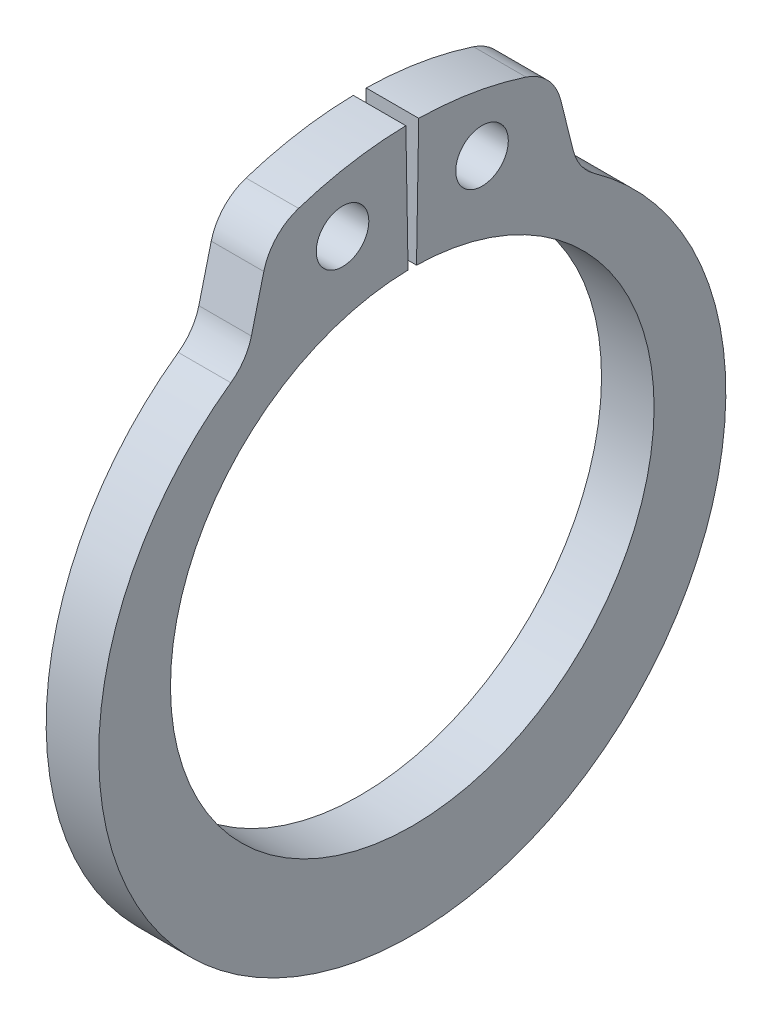
SolidWorks part; units mm, degrees
material "Cast Carbon Steel"
ref_plane "Front" through (0, 0, 0) normal (0, 0, 1) x (1, 0, 0)
ref_plane "Top" through (0, 0, 0) normal (0, 1, 0) x (1, 0, 0)
ref_plane "Right" through (0, 0, 0) normal (1, 0, 0) x (0, 0, -1)
sketch "Sketch1" plane through (0, 0, 0) normal (1, 0, 0) x (0, 0, -1)
  line L0 (0, 0) -> (0, 5.842) construction
  line L1 (-0.102, 5.8411) -> (-0.1552, 8.8886)
  line L2 (-0.1552, 8.8886) -> (-3.268, 8.8343) construction
  line L3 (-3.268, 8.8343) -> (-4.0054, 5.8768) construction
  line L4 (0.1552, 8.8886) -> (0.102, 5.8411)
  line L5 (0.1552, 8.8886) -> (3.268, 8.8343) construction
  line L6 (3.268, 8.8343) -> (4.0054, 5.8768) construction
  line L7 (-4.0054, 5.8768) -> (-3.2901, 4.8274) construction
  line L8 (4.0054, 5.8768) -> (3.2901, 4.8274) construction
  line L9 (0, -5.842) -> (0, -8.128) construction
  line L10 (-3.268, 8.8343) -> (-0.102, 5.8411) construction
  line L11 (-5.842, 0) -> (5.842, 0) construction
  line L12 (0, 5.842) -> (0, 8.89) construction
  line L13 (3.4253, 8.2036) -> (4.0054, 5.8768)
  line L14 (-3.4253, 8.2036) -> (-4.0054, 5.8768)
  circle A0 centre (0, 0) radius 5.842 construction
  arc A1 (-0.102, 5.8411) -> (0.102, 5.8411) centre (0, 0) ccw
  circle A2 centre (0, -0.5528) radius 7.5752 construction
  circle A3 centre (0, 0) radius 8.89 construction
  circle A4 centre (-1.685, 7.3377) radius 0.635
  circle A5 centre (1.685, 7.3377) radius 0.635
  arc A6 (-4.0054, 5.8768) -> (4.0054, 5.8768) centre (0, -0.5528) ccw
  arc A7 (0.1552, 8.8886) -> (3.4253, 8.2036) centre (0, 0) cw
  arc A8 (-0.1552, 8.8886) -> (-3.4253, 8.2036) centre (0, 0) ccw
  dimension "D1" = 75
  dimension "A" = 11.684
  dimension "L" = 17.78
  dimension "Hole" = 1.27
  dimension "Smin" = 1.27
  dimension "Smax" = 2.286
  dimension "H" = 3.048
  dimension "Angle" = 1
extrude "Extrude1" add sketch "Sketch1" along normal mid plane 1.27
fillet "Fillet1" radius 1.27 4 edges at (0, 5.8768, 4.0054) (0, 8.2036, 3.4253) (0, 8.2036, -3.4253) (0, 5.8768, -4.0054)
sketch "Sketch2" plane through (0, 0, 0) normal (0, 0, 1) x (1, 0, 0)
  line L0 (-3.556, 0) -> (10.668, 0)
  line L1 (10.668, 0) -> (10.668, -6.35)
  line L3 (10.668, -6.35) -> (0.7112, -6.35)
  line L4 (0.7112, -6.35) -> (0.7112, -5.9436)
  line L5 (0.7112, -5.9436) -> (-0.7112, -5.9436)
  line L6 (-0.7112, -5.9436) -> (-0.7112, -6.35)
  line L7 (-0.7112, -6.35) -> (-3.556, -6.35) construction
  line L8 (-3.556, -6.35) -> (-3.556, 0) construction
  line L9 (0, -5.9436) -> (0, 0) construction
  line L10 (10.668, 0) -> (14.0551, 0) construction
  line L11 (-0.7112, -6.35) -> (-3.3528, -6.35)
  line L12 (-3.3528, -6.35) -> (-3.556, -6.1468)
  line L13 (-3.556, -6.1468) -> (-3.556, 0)
  point P14 (-0.7112, -6.1468)
  dimension "D2" = 14.224
  dimension "D3" = 3.556
  dimension "D4" = 45
revolve "Revolve1" [suppressed] add sketch "Sketch2" angle 360 about L10
equation "\"D2@Sketch2\" = \"W@Sketch2\"*10"
equation "\"D3@Sketch2\" = \"D2@Sketch2\"/4"
